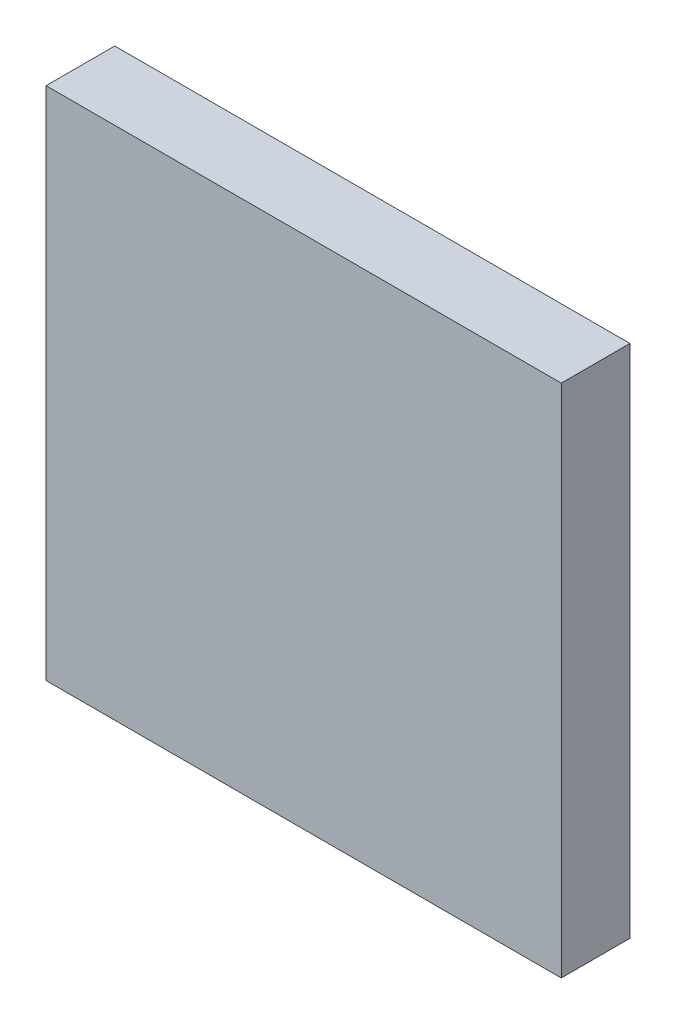
SolidWorks part; units mm, degrees
material "ABS"
ref_plane "Front Plane" through (0, 0, 0) normal (0, 0, 1) x (1, 0, 0)
ref_plane "Top Plane" through (0, 0, 0) normal (0, 1, 0) x (1, 0, 0)
ref_plane "Right Plane" through (0, 0, 0) normal (1, 0, 0) x (0, 0, -1)
ref_plane "Plane1" through (0, 0, 150) normal (0, 0, 1) x (1, 0, 0)
sketch "Sketch16" plane through (0, 0, 150) normal (0, 0, 1) x (1, 0, 0)
  line L1 (-75, 0) -> (75, 0)
  line L2 (-75, 0) -> (-75, -150)
  line L3 (-75, -150) -> (75, -150)
  line L4 (75, 0) -> (75, -150)
  line L5 (-75, 0) -> (75, -150) construction
  line L6 (-75, -150) -> (75, 0) construction
  point P0 (0, -75)
  point P5 (0, -150)
  dimension "D1" = 150
  dimension "D2" = 150
extrude "Boss-Extrude6" add sketch "Sketch16" along normal blind 20 separate body
